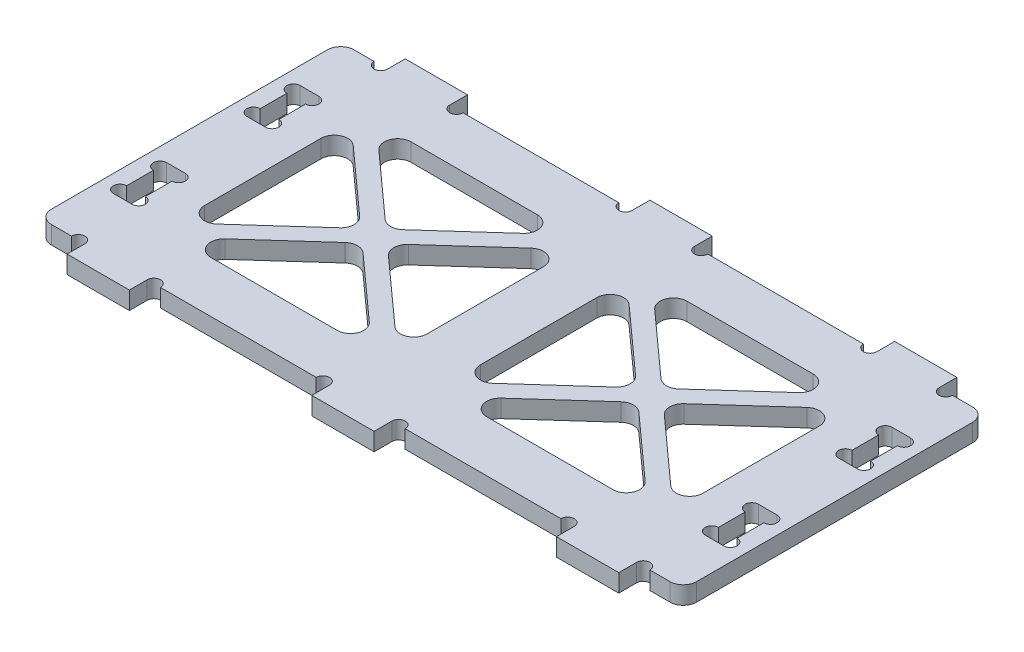
SolidWorks part; units mm, degrees
ref_plane "前视基准面" through (0, 0, 0) normal (0, 0, 1) x (1, 0, 0)
ref_plane "上视基准面" through (0, 0, 0) normal (0, 1, 0) x (1, 0, 0)
ref_plane "右视基准面" through (0, 0, 0) normal (1, 0, 0) x (0, 0, -1)
other "Configuration Table"
sketch "草图1" plane through (0, 0, 0) normal (0, 1, 0) x (1, 0, 0)
  line L0 (0, 30.6829) -> (0, -37.3171) construction
  line L1 (-72.5, -34) -> (72.5, -34)
  line L2 (-72.5, -34) -> (-72.5, 34)
  line L3 (-72.5, 34) -> (72.5, 34)
  line L4 (72.5, -34) -> (72.5, 34)
  line L5 (-72.5, -34) -> (72.5, 34) construction
  line L6 (-72.5, 34) -> (72.5, -34) construction
  line L7 (48, 38) -> (48, 34)
  line L8 (-7, 38) -> (7, 38)
  line L9 (-7, 38) -> (-7, 34)
  line L10 (-7, 34) -> (7, 34)
  line L11 (7, 38) -> (7, 34)
  line L12 (-7, 38) -> (7, 34) construction
  line L13 (-7, 34) -> (7, 38) construction
  line L14 (48, 38) -> (62, 38)
  line L15 (62, 38) -> (62, 34)
  line L16 (-62, 38) -> (-62, 34)
  line L17 (-48, 38) -> (-62, 38)
  line L18 (-48, 38) -> (-48, 34)
  line L19 (-72.5, 0) -> (72.5, 0) construction
  line L20 (62, -38) -> (62, -34)
  line L21 (48, -38) -> (62, -38)
  line L22 (48, -38) -> (48, -34)
  line L23 (-7, -34) -> (7, -38) construction
  line L24 (-7, -38) -> (7, -34) construction
  line L25 (7, -38) -> (7, -34)
  line L26 (-7, -38) -> (-7, -34)
  line L27 (-7, -38) -> (7, -38)
  line L28 (-48, -38) -> (-48, -34)
  line L29 (-48, -38) -> (-62, -38)
  line L30 (-62, -38) -> (-62, -34)
  point P0 (0, 0)
  point P7 (0, 36)
  point P31 (0, -36)
  dimension "D1" = 145
  dimension "D2" = 68
  dimension "D3" = 4
  dimension "D4" = 14
  dimension "D6" = 55
  dimension "D5" = 2
extrude "凸台-拉伸1" add sketch "草图1" along normal blind 4 contours L30 L29 L28 L1 | L1 L4 L3 L2 | L26 L27 L25 L1 | L22 L21 L20 L1 | L18 L17 L16 L3 | L15 L14 L7 L3 | L9 L8 L11 L10
sketch "草图2" plane through (0, 4, 0) normal (0, 1, 0) x (1, 0, 0)
  line L0 (-72.5, 34) -> (-62, 34) construction
  line L1 (-48, 34) -> (-7, 34) construction
  line L2 (-72.5, -34) -> (-62, -34) construction
  line L4 (-48, -34) -> (-7, -34) construction
  line L5 (7, 34) -> (48, 34) construction
  line L6 (7, -34) -> (48, -34) construction
  line L7 (62, -34) -> (72.5, -34) construction
  line L8 (62, 34) -> (72.5, 34) construction
  circle A0 centre (-63.5, 34) radius 1.5
  circle A1 centre (-46.5, 34) radius 1.5
  circle A2 centre (-8.5, 34) radius 1.5
  circle A3 centre (-63.5, -34) radius 1.5
  circle A5 centre (-46.5, -34) radius 1.5
  circle A6 centre (-8.5, -34) radius 1.5
  circle A7 centre (8.5, 34) radius 1.5
  circle A8 centre (46.5, 34) radius 1.5
  circle A9 centre (46.5, -34) radius 1.5
  circle A10 centre (8.5, -34) radius 1.5
  circle A11 centre (63.5, -34) radius 1.5
  circle A12 centre (63.5, 34) radius 1.5
  dimension "D1" = 3
extrude "切除-拉伸1" cut sketch "草图2" against normal blind 4
sketch "草图3" plane through (0, 4, 0) normal (0, 1, 0) x (1, 0, 0)
  line L0 (72.5, 0) -> (0, 0) construction
  line L1 (72.5, -34) -> (72.5, 34) construction
  line L2 (66.5, 21) -> (66.5, 9) construction
  line L3 (64.4, 21) -> (68.6, 21)
  line L4 (64.4, 21) -> (64.4, 9)
  line L5 (64.4, 9) -> (68.6, 9)
  line L6 (68.6, 21) -> (68.6, 9)
  line L7 (66.5, -21) -> (66.5, -9) construction
  line L8 (68.6, -21) -> (68.6, -9)
  line L9 (64.4, -9) -> (68.6, -9)
  line L10 (64.4, -21) -> (64.4, -9)
  line L11 (64.4, -21) -> (68.6, -21)
  circle A0 centre (64.4, 19.5) radius 1.5
  circle A1 centre (68.6, 19.5) radius 1.5
  circle A2 centre (64.4, 10.5) radius 1.5
  circle A3 centre (68.6, 10.5) radius 1.5
  circle A4 centre (68.6, -10.5) radius 1.5
  circle A5 centre (64.4, -10.5) radius 1.5
  circle A6 centre (68.6, -19.5) radius 1.5
  circle A7 centre (64.4, -19.5) radius 1.5
  dimension "D4" = 3
  dimension "D1" = 6
  dimension "D2" = 12
  dimension "D3" = 4.2
  dimension "D5" = 18
extrude "切除-拉伸2" cut sketch "草图3" against normal blind 10 contours A3 L6 A1 L3 A0 L4 A2 L5 | L4 A2 | L4 A2 | L4 A0 | L4 A0 | L6 A1 | L6 A1 | L6 A3 | L6 A3 | A7 L10 | A7 L10 | L10 A7 L11 A6 L8 A4 L9 A5 | A6 L8 | A5 L10 | A4 L8 | A4 L8 | A6 L8 | A5 L10
mirror "镜向1" about plane through (0, 0, 0) normal (1, 0, 0) of "切除-拉伸2"
sketch "草图4" plane through (0, 4, 0) normal (0, 1, 0) x (1, 0, 0)
  line L0 (36.5339, 0) -> (-36.5339, 0) construction
  line L1 (0, 0) -> (0, 23.6472) construction
  line L2 (-56, 22.5) -> (-6, -22.5) construction
  line L3 (-56, 22.5) -> (-6, 22.5)
  line L4 (-56, 22.5) -> (-56, -22.5)
  line L5 (-56, -22.5) -> (-6, -22.5)
  line L6 (-6, 22.5) -> (-6, -22.5)
  line L7 (-6, 22.5) -> (-56, -22.5) construction
  line L8 (-53.0103, 22.5) -> (-6, -19.8093)
  line L9 (-56, 19.8093) -> (-8.9897, -22.5)
  line L10 (-56, 22.5) -> (-31, 0)
  line L11 (-31, 0) -> (-56, -22.5)
  line L12 (-8.9897, 22.5) -> (-56, -19.8093)
  line L13 (-6, 19.8093) -> (-53.0103, -22.5)
  line L14 (6, 22.5) -> (56, -22.5) construction
  line L15 (56, 22.5) -> (6, -22.5) construction
  line L16 (6, 19.8093) -> (53.0103, -22.5)
  line L17 (8.9897, 22.5) -> (56, -19.8093)
  line L18 (31, 0) -> (56, -22.5)
  line L19 (56, 22.5) -> (31, 0)
  line L20 (56, 19.8093) -> (8.9897, -22.5)
  line L21 (53.0103, 22.5) -> (6, -19.8093)
  line L22 (6, 22.5) -> (6, -22.5)
  line L23 (56, -22.5) -> (6, -22.5)
  line L24 (56, 22.5) -> (56, -22.5)
  line L25 (56, 22.5) -> (6, 22.5)
  dimension "D1" = 45
  dimension "D2" = 50
  dimension "D3" = 4
  dimension "D4" = 4
  dimension "D5" = 2
  dimension "D6" = 2
  dimension "D7" = 12
extrude "切除-拉伸3" cut sketch "草图4" against normal blind 5 contours L12 L9 L4 | L12 L3 L8 | L6 L13 L8 | L9 L13 L5 | L16 L22 L21 | L21 L25 L17 | L24 L20 L17 | L23 L16 L20
fillet "圆角1" radius 3 24 edges at (8.9897, 2, 22.5) (53.0103, 2, 22.5) (56, 2, 19.8093) (56, 2, -19.8093) (33.9897, 2, 0) (31, 2, 2.6907) (31, 2, -2.6907) (53.0103, 2, -22.5) (8.9897, 2, -22.5) (6, 2, 19.8093) (28.0103, 2, 0) (6, 2, -19.8093) (-8.9897, 2, 22.5) (-53.0103, 2, 22.5) (-56, 2, 19.8093) (-6, 2, -19.8093) (-8.9897, 2, -22.5) (-53.0103, 2, -22.5) (-31, 2, 2.6907) (-28.0103, 2, 0) (-31, 2, -2.6907) (-33.9897, 2, 0) (-56, 2, -19.8093) (-6, 2, 19.8093)
fillet "圆角2" radius 3 4 edges at (72.5, 2, -34) (72.5, 2, 34) (-72.5, 2, 34) (-72.5, 2, -34)
